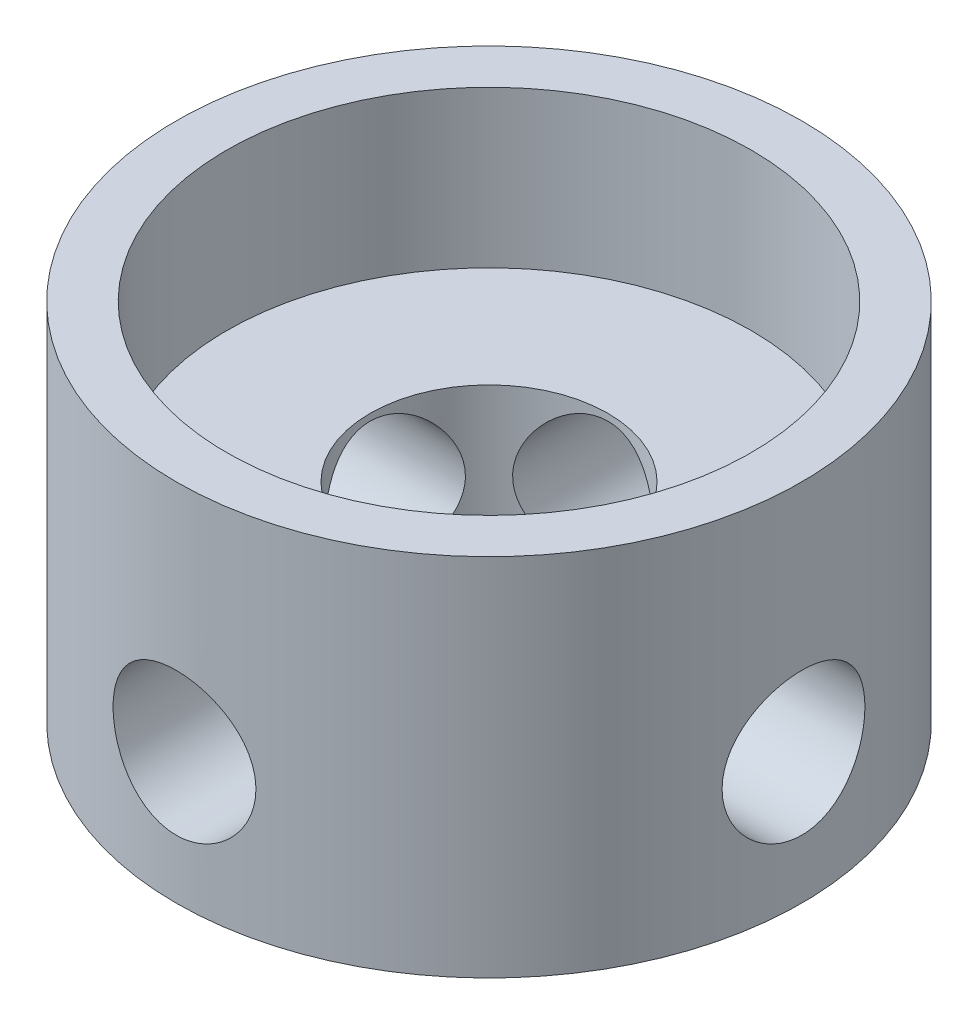
SolidWorks part; units mm, degrees
ref_plane "Front Plane" through (0, 0, 0) normal (0, 0, 1) x (1, 0, 0)
ref_plane "Top Plane" through (0, 0, 0) normal (0, 1, 0) x (1, 0, 0)
ref_plane "Right Plane" through (0, 0, 0) normal (1, 0, 0) x (0, 0, -1)
sketch "Sketch1" plane through (0, 0, 0) normal (0, 1, 0) x (1, 0, 0)
  circle A0 centre (0, 0) radius 2.8956
  circle A1 centre (0, 0) radius 7.62
  dimension "D1" = 5.7912
  dimension "D2" = 15.24
extrude "Boss-Extrude1" add sketch "Sketch1" along normal blind 5.08
sketch "Sketch2" plane through (0, 5.08, 0) normal (0, 1, 0) x (1, 0, 0)
  circle A0 centre (0, 0) radius 6.3881
  circle A1 centre (0, 0) radius 7.62
  dimension "D1" = 12.7762
  dimension "D2" = 15.24
extrude "Boss-Extrude2" add sketch "Sketch2" along normal blind 3.81
sketch "Sketch3" plane through (0, 0, 0) normal (0, 0, 1) x (1, 0, 0)
  line L0 (-7.62, 0) -> (7.62, 0) construction
  circle A0 centre (0, 3.175) radius 1.7399
  point P5 (0, 0)
  dimension "D2" = 3.4798
  dimension "D1" = 3.175
extrude "Cut-Extrude1" cut sketch "Sketch3" against normal mid plane 25.4
sketch "Sketch4" plane through (0, 0, 0) normal (1, 0, 0) x (0, 0, -1)
  line L0 (-7.62, 0) -> (7.62, 0) construction
  circle A0 centre (0, 3.175) radius 1.7399
  point P2 (0, 0)
  dimension "D2" = 3.4798
  dimension "D1" = 3.175
extrude "Cut-Extrude2" cut sketch "Sketch4" against normal mid plane 25.4
